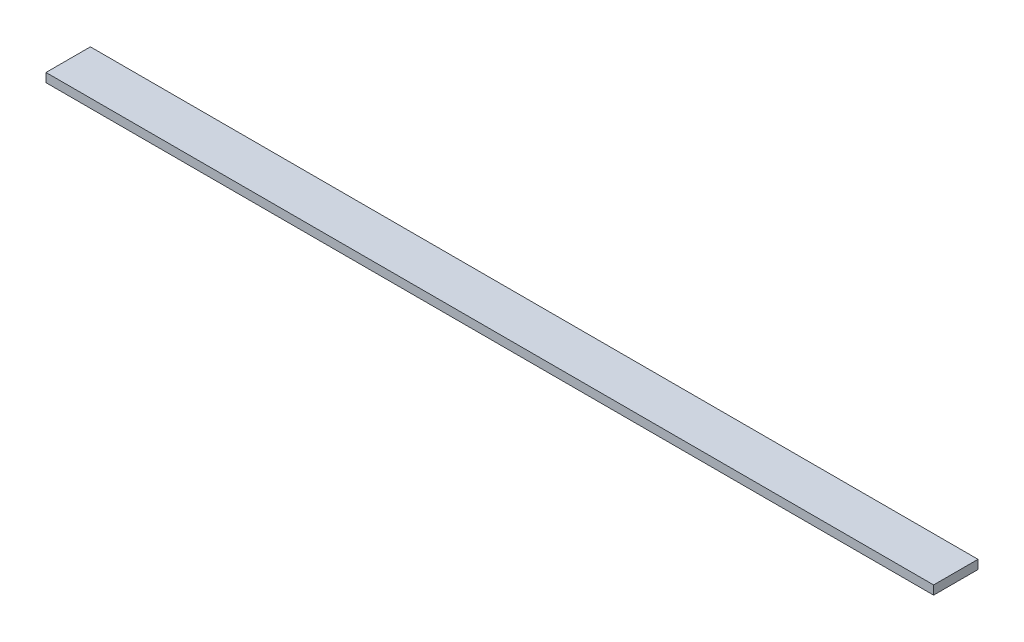
SolidWorks part; units mm, degrees
ref_plane "Front Plane" through (0, 0, 0) normal (0, 0, 1) x (1, 0, 0)
ref_plane "Top Plane" through (0, 0, 0) normal (0, 1, 0) x (1, 0, 0)
ref_plane "Right Plane" through (0, 0, 0) normal (1, 0, 0) x (0, 0, -1)
other "Configuration Table"
sketch "Sketch1" plane through (0, 0, 0) normal (0, 0, 1) x (1, 0, 0)
  line L1 (150, 1040) -> (550, 1040)
  line L2 (150, 1040) -> (150, 1044)
  line L3 (150, 1044) -> (550, 1044)
  line L4 (550, 1040) -> (550, 1044)
extrude "PACK_sarjor_alt_tutucu_ray_1_1" add sketch "Sketch1" against normal blind 20 from offset 780 separate body
